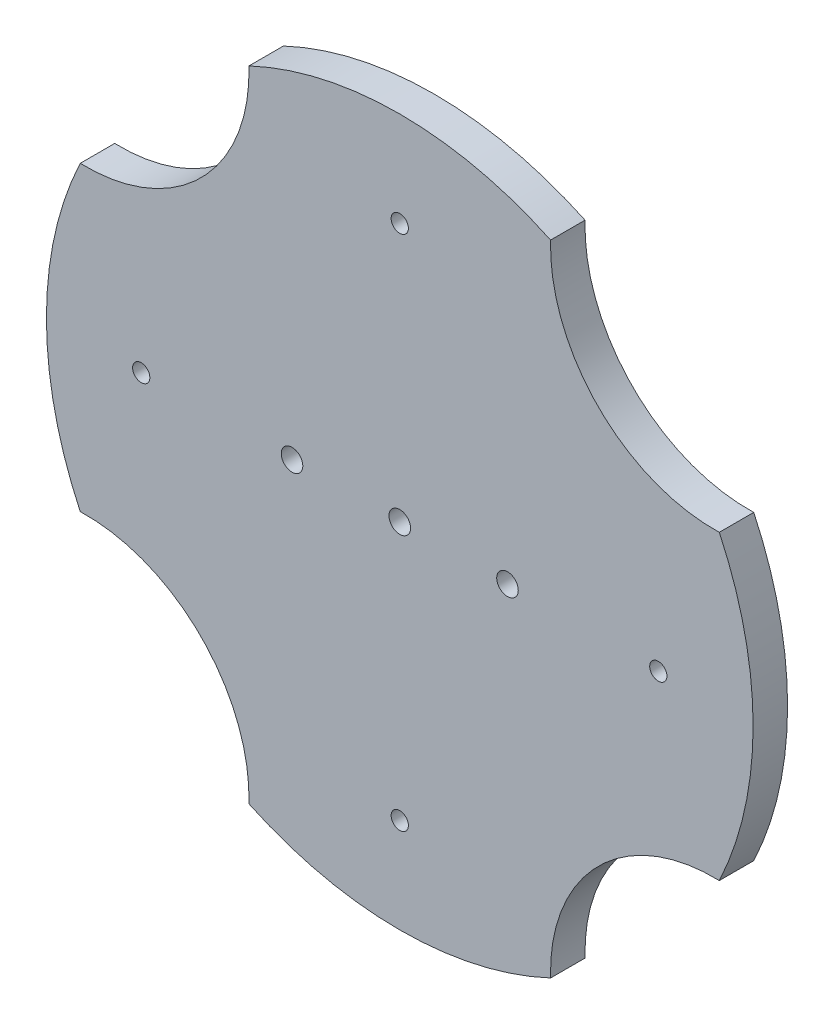
SolidWorks part; units mm, degrees
ref_plane "Front Plane" through (0, 0, 0) normal (0, 0, 1) x (1, 0, 0)
ref_plane "Top Plane" through (0, 0, 0) normal (0, 1, 0) x (1, 0, 0)
ref_plane "Right Plane" through (0, 0, 0) normal (1, 0, 0) x (0, 0, -1)
sketch "Sketch1" plane through (0, 0, 0) normal (0, 0, 1) x (1, 0, 0)
  circle A0 centre (0, 0) radius 82
  dimension "D1" = 164
extrude "Boss-Extrude1" add sketch "Sketch1" along normal blind 8
sketch "Sketch2" plane through (0, 0, 8) normal (0, 0, 1) x (1, 0, 0)
  circle A0 centre (0, 60) radius 2
  dimension "D1" = 4
  dimension "D2" = 60
extrude "Cut-Extrude1" cut sketch "Sketch2" against normal blind 15
pattern_circular "CirPattern2" count 4 every 90 about axis through (0, 0, 0) along (0, 0, 1) of "Cut-Extrude1"
sketch "Sketch7" plane through (0, 0, 0) normal (0, 0, -1) x (-1, 0, 0)
  line L7 (1.7885, 63.6242) -> (-2.2444, 63.3609)
  line L8 (-2.2444, 63.3609) -> (-4.0329, 59.7368)
  line L9 (-4.0329, 59.7368) -> (-1.7885, 56.3758)
  line L10 (-1.7885, 56.3758) -> (2.2444, 56.6391)
  line L11 (2.2444, 56.6391) -> (4.0329, 60.2632)
  line L12 (4.0329, 60.2632) -> (1.7885, 63.6242)
  circle A0 centre (0, 60) radius 3.5 construction
  point P30 (36.3101, 9.0679)
  dimension "D1" = 7
extrude "Cut-Extrude3" cut sketch "Sketch7" against normal blind 3.2
pattern_circular "CirPattern3" count 4 every 90 about axis through (0, 0, 0) along (0, 0, 1) of "Cut-Extrude3"
sketch "Sketch10" plane through (0, 0, 8) normal (0, 0, 1) x (1, 0, 0)
  circle A0 centre (0, 0) radius 2.5
  circle A1 centre (25, 0) radius 2.5
  circle A2 centre (-25, 0) radius 2.5
  dimension "D1" = 5
  dimension "D2" = 5
  dimension "D3" = 5
  dimension "D4" = 25
  dimension "D5" = 25
extrude "Cut-Extrude4" cut sketch "Sketch10" against normal blind 10
sketch "Sketch11" plane through (0, 0, 8) normal (0, 0, 1) x (1, 0, 0)
  line L0 (0, 0) -> (57.9828, 57.9828) construction
  line L1 (57.9828, 57.9828) -> (57.9828, -57.9828) construction
  line L2 (57.9828, -57.9828) -> (-57.9828, -57.9828) construction
  line L3 (-57.9828, -57.9828) -> (-57.9828, 57.9828) construction
  line L4 (-57.9828, 57.9828) -> (57.9828, 57.9828) construction
  circle A0 centre (0, 0) radius 82 construction
  arc A1 (-35.0008, 74.1548) -> (-74.1548, 35.0008) centre (-72.9828, 72.9828) cw
  arc A2 (-74.1548, 35.0008) -> (-35.0008, 74.1548) centre (0, 0) cw
  dimension "D3" = 38
  dimension "D1" = 15
  dimension "D2" = 15
extrude "Cut-Extrude5" cut sketch "Sketch11" against normal blind 10
pattern_circular "CirPattern4" count 4 every 90 about axis through (0, 0, 0) along (0, 0, 1) of "Cut-Extrude5"
